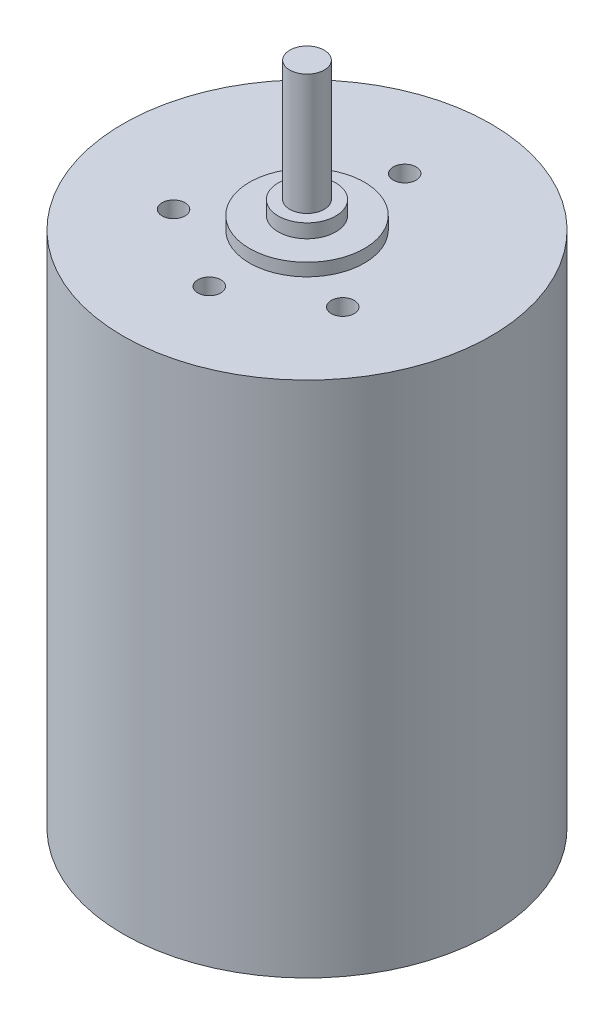
SolidWorks part; units mm, degrees
ref_plane "Front Plane" through (0, 0, 0) normal (0, 0, 1) x (1, 0, 0)
ref_plane "Top Plane" through (0, 0, 0) normal (0, 1, 0) x (1, 0, 0)
ref_plane "Right Plane" through (0, 0, 0) normal (1, 0, 0) x (0, 0, -1)
sketch "Sketch1" plane through (0, 0, 0) normal (0, 1, 0) x (1, 0, 0)
  circle A0 centre (0, 0) radius 16
  dimension "D1" = 32
extrude "Boss-Extrude1" add sketch "Sketch1" against normal blind 45.05
sketch "Sketch3" plane through (0, 0, 0) normal (0, 1, 0) x (1, 0, 0)
  circle A0 centre (0, 0) radius 5
  dimension "D1" = 10
extrude "Boss-Extrude2" add sketch "Sketch3" along normal blind 1.1
sketch "Sketch4" plane through (0, 1.1, 0) normal (0, 1, 0) x (1, 0, 0)
  circle A0 centre (0, 0) radius 2.5
  dimension "D1" = 5
extrude "Boss-Extrude3" add sketch "Sketch4" along normal blind 1.2
sketch "Sketch5" plane through (0, 2.3, 0) normal (0, 1, 0) x (1, 0, 0)
  circle A0 centre (0, 0) radius 1.5
  dimension "D1" = 3
extrude "Boss-Extrude4" add sketch "Sketch5" along normal blind 10.5
sketch "Sketch6" plane through (0, 0, 0) normal (0, 1, 0) x (1, 0, 0)
  line L0 (0, 8.5) -> (0, -8.5) construction
  line L1 (-7.3612, -4.25) -> (0, 0) construction
  line L2 (0, 0) -> (7.3612, -4.25) construction
  circle A0 centre (0, 8.5) radius 1
  circle A1 centre (0, -8.5) radius 1
  circle A2 centre (0, 0) radius 8.5 construction
  circle A3 centre (-7.3612, -4.25) radius 1
  circle A4 centre (7.3612, -4.25) radius 1
  point P4 (0, 0)
  dimension "D2" = 2
  dimension "D1" = 17
  dimension "D3" = 120
  dimension "D4" = 60
extrude "Cut-Extrude1" cut sketch "Sketch6" against normal blind 3.6
